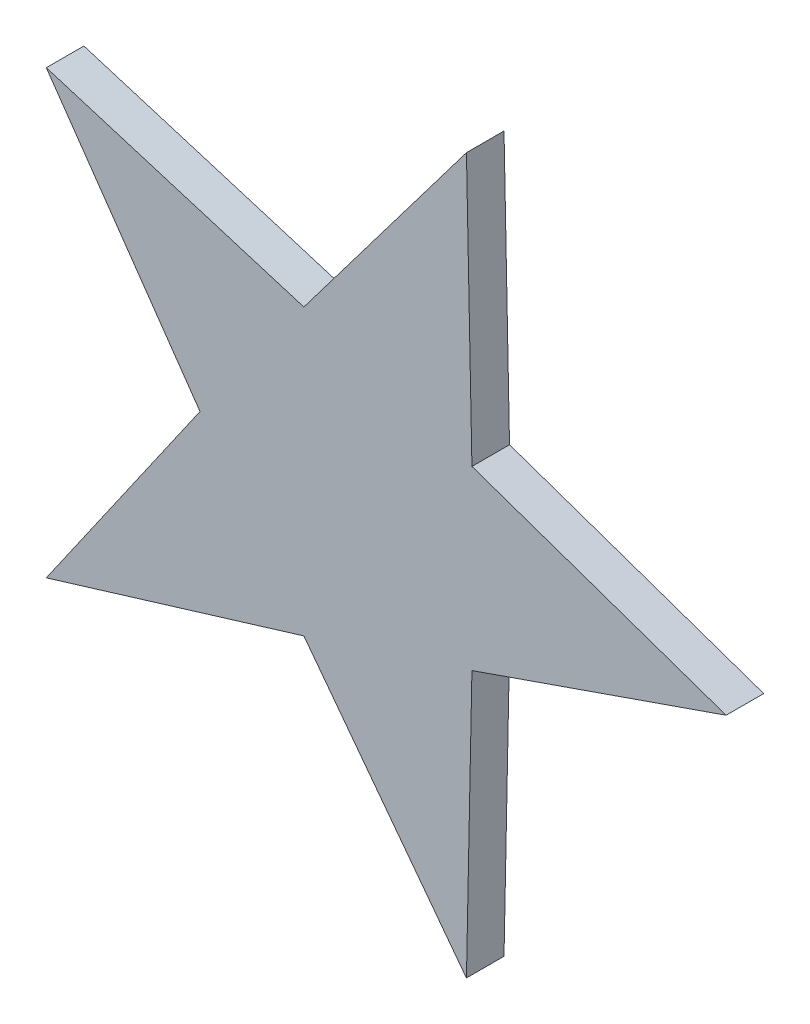
SolidWorks part; units mm, degrees
ref_plane "前视基准面" through (0, 0, 0) normal (0, 0, 1) x (1, 0, 0)
ref_plane "上视基准面" through (0, 0, 0) normal (0, 1, 0) x (1, 0, 0)
ref_plane "右视基准面" through (0, 0, 0) normal (1, 0, 0) x (0, 0, -1)
other "Configuration Table"
sketch "草图1" plane through (0, 0, 0) normal (0, 0, 1) x (1, 0, 0)
  line L0 (500, 0) -> (161.8, 117.6)
  line L1 (161.8, 117.6) -> (154.5, 475.5)
  line L2 (154.5, 475.5) -> (-61.8, 189.5)
  line L3 (-61.8, 189.5) -> (-404.5, 293.9)
  line L4 (-404.5, 293.9) -> (-200, 0)
  line L5 (-200, 0) -> (-404.5, -293.9)
  line L6 (-404.5, -293.9) -> (-61.8, -189.5)
  line L7 (-61.8, -189.5) -> (154.5, -475.5)
  line L8 (154.5, -475.5) -> (161.8, -117.6)
  line L9 (161.8, -117.6) -> (500, 0)
extrude "凸台-拉伸1" add sketch "草图1" along normal blind 50
